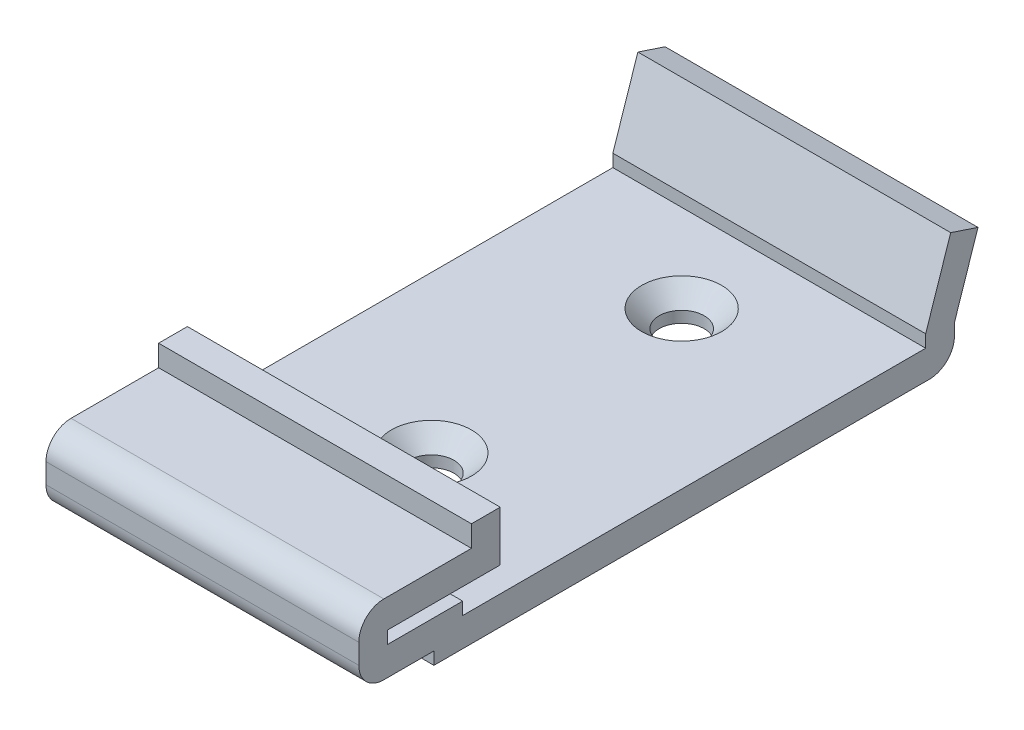
SolidWorks part; units mm, degrees
ref_plane "前视基准面" through (0, 0, 0) normal (0, 0, 1) x (1, 0, 0)
ref_plane "上视基准面" through (0, 0, 0) normal (0, 1, 0) x (1, 0, 0)
ref_plane "右视基准面" through (0, 0, 0) normal (1, 0, 0) x (0, 0, -1)
sketch "草图1" plane through (0, 0, 0) normal (1, 0, 0) x (0, 0, -1)
  line L0 (0, 4) -> (0, 0)
  line L1 (0, 0) -> (-9, 0)
  line L2 (-9, 0) -> (-9, -1)
  line L3 (-9, -1) -> (-3, -1)
  line L4 (-3, -1) -> (-3, -2)
  line L5 (-3, -2) -> (34, -2)
  line L6 (34, -2) -> (34, -1)
  line L7 (34, -1) -> (36, 5)
  line L8 (-2.3, 4) -> (-2.3, 2.3)
  line L9 (-2.3, 2.3) -> (-11.3, 2.3)
  line L10 (-11.3, 2.3) -> (-11.3, -3.3)
  line L11 (-11.3, -3.3) -> (-5.3, -3.3)
  line L12 (-5.3, -3.3) -> (-5.3, -4.3)
  line L13 (-5.3, -4.3) -> (36.3, -4.3)
  line L14 (36.3, -4.3) -> (36.3, -1.3732)
  line L15 (36.3, -1.3732) -> (38.182, 4.2727)
  line L16 (0, 4) -> (-2.3, 4)
  line L17 (36, 5) -> (38.182, 4.2727)
  dimension "D1" = 4
  dimension "D2" = 9
  dimension "D3" = 1
  dimension "D4" = 6
  dimension "D5" = 1
  dimension "D6" = 37
  dimension "D7" = 1
  dimension "D8" = 2
  dimension "D9" = 6
  dimension "D10" = 2.3
extrude "凸台-拉伸1" add sketch "草图1" along normal mid plane 10
fillet "圆角1" radius 2 3 edges at (0, -4.3, -36.3) (0, -3.3, 11.3) (0, 2.3, 11.3)
sketch "草图6" [suppressed] plane through (5, 0, 0) normal (1, 0, 0) x (0, 0, -1)
  line L18 (-5.3, -4.3) -> (34.3, -4.3)
  line L19 (36.3, -2.3) -> (36.3, -1.3732)
  line L20 (36.3, -1.3732) -> (38.182, 4.2727)
  line L21 (38.182, 4.2727) -> (36, 5)
  line L22 (36, 5) -> (34, -1)
  line L23 (34, -1) -> (34, -2)
  line L24 (34, -2) -> (-3, -2)
  line L25 (-3, -2) -> (-3, -1)
  line L26 (-3, -1) -> (-9, -1)
  line L27 (-9, -1) -> (-9, 0)
  line L28 (-9, 0) -> (0, 0)
  line L29 (0, 0) -> (0, 4)
  line L30 (0, 4) -> (-2.3, 4)
  line L31 (-2.3, 4) -> (-2.3, 2.3)
  line L32 (-2.3, 2.3) -> (-9.3, 2.3)
  line L33 (-11.3, 0.3) -> (-11.3, -1.3)
  line L34 (-9.3, -3.3) -> (-5.3, -3.3)
  line L35 (-5.3, -3.3) -> (-5.3, -4.3)
  line L36 (-5.3, -4.3) -> (34.3, -4.3)
  line L37 (36.3, -2.3) -> (36.3, -1.3732)
  line L38 (36.3, -1.3732) -> (38.182, 4.2727)
  line L39 (38.182, 4.2727) -> (36, 5)
  line L40 (36, 5) -> (34, -1)
  line L41 (34, -1) -> (34, -2)
  line L42 (34, -2) -> (-3, -2)
  line L43 (-3, -2) -> (-3, -1)
  line L44 (-3, -1) -> (-9, -1)
  line L45 (-9, -1) -> (-9, 0)
  line L46 (-9, 0) -> (0, 0)
  line L47 (0, 0) -> (0, 4)
  line L48 (0, 4) -> (-2.3, 4)
  line L49 (-2.3, 4) -> (-2.3, 2.3)
  line L50 (-2.3, 2.3) -> (-9.3, 2.3)
  line L51 (-11.3, 0.3) -> (-11.3, -1.3)
  line L52 (-9.3, -3.3) -> (-5.3, -3.3)
  line L53 (-5.3, -3.3) -> (-5.3, -4.3)
  arc A3 (34.3, -4.3) -> (36.3, -2.3) centre (34.3, -2.3) ccw
  arc A4 (-9.3, 2.3) -> (-11.3, 0.3) centre (-9.3, 0.3) ccw
  arc A5 (-11.3, -1.3) -> (-9.3, -3.3) centre (-9.3, -1.3) ccw
  arc A6 (34.3, -4.3) -> (36.3, -2.3) centre (34.3, -2.3) ccw
  arc A7 (-9.3, 2.3) -> (-11.3, 0.3) centre (-9.3, 0.3) ccw
  arc A8 (-11.3, -1.3) -> (-9.3, -3.3) centre (-9.3, -1.3) ccw
  dimension "D1" = 0
extrude "凸台-拉伸2" [suppressed] add sketch "草图6" along normal blind 34
hole_wizard "打孔尺寸开槽半沉头螺钉的类型2" [suppressed] positions "草图4" profile "草图5" countersink size "M3" standard "GB"
sketch "草图4" plane through (0, -2, 0) normal (0, 1, 0) x (1, 0, 0)
  line L0 (17, 0) -> (17, 18.0224) construction
  line L2 (39, -11.3) -> (-5, -11.3) construction
  line L3 (39, 0) -> (-5, 0) construction
  point P0 (8, 8.7)
  point P2 (26, 8.7)
  dimension "D1" = 18
  dimension "D2" = 20
sketch "草图5" plane through (8, -2, -8.7) normal (1, 0, 0) x (0, 0, 1)
  line L0 (0, 0) -> (0, 2.3)
  line L1 (0, 2.3) -> (1.8, 2.3)
  line L2 (1.8, 2.3) -> (1.8, 1.4)
  line L3 (1.8, 1.4) -> (3.2, 0)
  line L5 (3.2, 0) -> (0, 0)
  line L6 (-1.8, 1.4) -> (-3.2, 0) construction
  line L11 (0, -6.35) -> (0, 107.95) construction
  dimension "通孔孔直径" = 3.6
  dimension "通孔孔深度" = 2.3
  dimension "近端锥形沉头孔直径" = 6.4
  dimension "近端锥形沉头孔角度" = 90
sketch "草图7" plane through (5, 0, 0) normal (1, 0, 0) x (0, 0, -1)
  line L18 (-5.3, -4.3) -> (34.3, -4.3)
  line L19 (36.3, -2.3) -> (36.3, -1.3732)
  line L20 (36.3, -1.3732) -> (38.182, 4.2727)
  line L21 (38.182, 4.2727) -> (36, 5)
  line L22 (36, 5) -> (34, -1)
  line L23 (34, -1) -> (34, -2)
  line L24 (34, -2) -> (-3, -2)
  line L25 (-3, -2) -> (-3, -1)
  line L26 (-3, -1) -> (-9, -1)
  line L27 (-9, -1) -> (-9, 0)
  line L28 (-9, 0) -> (0, 0)
  line L29 (0, 0) -> (0, 4)
  line L30 (0, 4) -> (-2.3, 4)
  line L31 (-2.3, 4) -> (-2.3, 2.3)
  line L32 (-2.3, 2.3) -> (-9.3, 2.3)
  line L33 (-11.3, 0.3) -> (-11.3, -1.3)
  line L34 (-9.3, -3.3) -> (-5.3, -3.3)
  line L35 (-5.3, -3.3) -> (-5.3, -4.3)
  line L36 (-5.3, -4.3) -> (34.3, -4.3)
  line L37 (36.3, -2.3) -> (36.3, -1.3732)
  line L38 (36.3, -1.3732) -> (38.182, 4.2727)
  line L39 (38.182, 4.2727) -> (36, 5)
  line L40 (36, 5) -> (34, -1)
  line L41 (34, -1) -> (34, -2)
  line L42 (34, -2) -> (-3, -2)
  line L43 (-3, -2) -> (-3, -1)
  line L44 (-3, -1) -> (-9, -1)
  line L45 (-9, -1) -> (-9, 0)
  line L46 (-9, 0) -> (0, 0)
  line L47 (0, 0) -> (0, 4)
  line L48 (0, 4) -> (-2.3, 4)
  line L49 (-2.3, 4) -> (-2.3, 2.3)
  line L50 (-2.3, 2.3) -> (-9.3, 2.3)
  line L51 (-11.3, 0.3) -> (-11.3, -1.3)
  line L52 (-9.3, -3.3) -> (-5.3, -3.3)
  line L53 (-5.3, -3.3) -> (-5.3, -4.3)
  arc A3 (34.3, -4.3) -> (36.3, -2.3) centre (34.3, -2.3) ccw
  arc A4 (-9.3, 2.3) -> (-11.3, 0.3) centre (-9.3, 0.3) ccw
  arc A5 (-11.3, -1.3) -> (-9.3, -3.3) centre (-9.3, -1.3) ccw
  arc A6 (34.3, -4.3) -> (36.3, -2.3) centre (34.3, -2.3) ccw
  arc A7 (-9.3, 2.3) -> (-11.3, 0.3) centre (-9.3, 0.3) ccw
  arc A8 (-11.3, -1.3) -> (-9.3, -3.3) centre (-9.3, -1.3) ccw
  dimension "D1" = 0
extrude "凸台-拉伸3" add sketch "草图7" along normal blind 15
hole_wizard "打孔尺寸开槽半沉头螺钉的类型1" positions "草图2" profile "草图3" countersink size "M3" standard "GB" end condition through all
sketch "草图2" plane through (0, -2, 0) normal (0, 1, 0) x (1, 0, 0)
  line L0 (7.5, 0) -> (7.5, 34) construction
  line L3 (7.5, 17) -> (-2.9749, 17) construction
  line L4 (20, 0) -> (-5, 0) construction
  line L5 (20, 34) -> (-5, 34) construction
  point P0 (7.5, 27)
  point P2 (7.5, 7)
  dimension "D1" = 20
sketch "草图3" plane through (7.5, -2, -27) normal (1, 0, 0) x (0, 0, 1)
  line L0 (0, 0) -> (0, 2.3)
  line L1 (0, 2.3) -> (1.8, 2.3)
  line L2 (1.8, 2.3) -> (1.8, 1.4)
  line L3 (1.8, 1.4) -> (3.2, 0)
  line L5 (3.2, 0) -> (0, 0)
  line L6 (-1.8, 1.4) -> (-3.2, 0) construction
  line L11 (0, -6.35) -> (0, 107.95) construction
  dimension "通孔孔直径" = 3.6
  dimension "通孔孔深度" = 2.3
  dimension "近端锥形沉头孔直径" = 6.4
  dimension "近端锥形沉头孔角度" = 90
